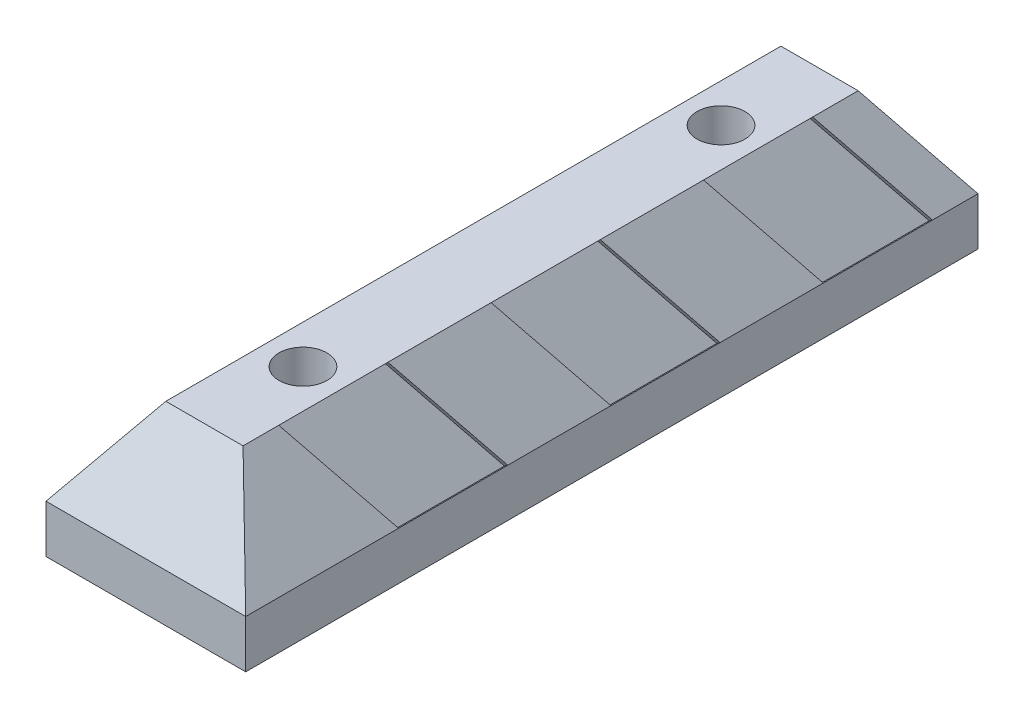
SolidWorks part; units mm, degrees
ref_plane "Alzado" through (0, 0, 0) normal (0, 0, 1) x (1, 0, 0)
ref_plane "Planta" through (0, 0, 0) normal (0, 1, 0) x (1, 0, 0)
ref_plane "Vista lateral" through (0, 0, 0) normal (1, 0, 0) x (0, 0, -1)
sketch "Croquis1" plane through (0, 0, 0) normal (0, 0, 1) x (1, 0, 0)
  line L1 (0, 0) -> (150, 0)
  line L2 (0, 0) -> (0, 102)
  line L3 (0, 102) -> (150, 102)
  line L4 (150, 0) -> (150, 102)
  dimension "D1" = 150
  dimension "D2" = 102
extrude "Saliente-Extruir1" add sketch "Croquis1" along normal blind 550
sketch "Croquis2" plane through (0, 0, 550) normal (0, 0, 1) x (1, 0, 0)
  line L0 (0, 36) -> (46, 102)
  line L1 (0, 102) -> (0, 0) construction
  line L2 (150, 102) -> (0, 102) construction
  line L3 (75, 102) -> (75, 0) construction
  line L4 (0, 0) -> (150, 0) construction
  line L5 (150, 36) -> (104, 102)
  line L6 (46, 102) -> (-6.7267, 105.185)
  line L7 (-6.7267, 105.185) -> (0, 36)
  line L8 (104, 102) -> (154.5473, 106.586)
  line L9 (154.5473, 106.586) -> (150, 36)
  dimension "D1" = 36
  dimension "D2" = 46
extrude "Cortar-Extruir1" cut sketch "Croquis2" against normal up to surface (550 mm away) up to face at (75, 51, 0)
sketch "Croquis3" plane through (0, 0, 0) normal (-1, 0, 0) x (0, 0, 1)
  line L0 (0, 36) -> (44, 102)
  line L1 (0, 102) -> (550, 102) construction
  line L2 (44, 102) -> (0, 102)
  line L3 (0, 102) -> (0, 36)
  line L4 (275, 102) -> (275, 0) construction
  line L5 (550, 0) -> (0, 0) construction
  line L6 (550, 36) -> (506, 102)
  line L7 (550, 102) -> (550, 36)
  line L8 (506, 102) -> (550, 102)
  dimension "D1" = 44
extrude "Cortar-Extruir2" cut sketch "Croquis3" against normal blind 500
sketch "Croquis4" plane through (-16.8875, 11.7701, 0) normal (-0.8204, 0.5718, 0) x (0, 0, 1)
  line L0 (34.1939, 29.5343) -> (78.1939, 109.9831)
  line L1 (0, 29.5343) -> (550, 29.5343) construction
  line L2 (44, 109.9831) -> (506, 109.9831) construction
  line L3 (78.1939, 109.9831) -> (160.1939, 109.9831)
  line L4 (160.1939, 109.9831) -> (116.1939, 29.5343)
  line L5 (116.1939, 29.5343) -> (34.1939, 29.5343)
  line L6 (44, 109.9831) -> (0, 29.5343) construction
  line L7 (193.7, 29.5343) -> (237.7, 109.9831)
  line L8 (237.7, 109.9831) -> (319.7, 109.9831)
  line L9 (319.7, 109.9831) -> (275.7, 29.5343)
  line L10 (275.7, 29.5343) -> (193.7, 29.5343)
  line L11 (353.2061, 29.5343) -> (397.2061, 109.9831)
  line L12 (397.2061, 109.9831) -> (479.2061, 109.9831)
  line L13 (479.2061, 109.9831) -> (435.2061, 29.5343)
  line L14 (435.2061, 29.5343) -> (353.2061, 29.5343)
  dimension "D1" = 30
  dimension "D2" = 82
  dimension "D3" = 82
  dimension "D4" = 68
  dimension "D5" = 82
  dimension "D6" = 68
extrude "Cortar-Extruir3" cut sketch "Croquis4" against normal blind 3
sketch "Croquis5" plane through (117.8455, 82.1347, 0) normal (0.8204, 0.5718, 0) x (0, 0, -1)
  line L0 (-78.1939, 24.2142) -> (-34.1939, -56.2346)
  line L1 (-44, 24.2142) -> (-506, 24.2142) construction
  line L2 (0, -56.2346) -> (-550, -56.2346) construction
  line L3 (-34.1939, -56.2346) -> (-116.1939, -56.2346)
  line L4 (-116.1939, -56.2346) -> (-160.1939, 24.2142)
  line L5 (-160.1939, 24.2142) -> (-78.1939, 24.2142)
  line L6 (0, -56.2346) -> (-44, 24.2142) construction
  line L7 (-193.7, -56.2346) -> (-237.7, 24.2142)
  line L8 (-237.7, 24.2142) -> (-319.7, 24.2142)
  line L9 (-319.7, 24.2142) -> (-275.7, -56.2346)
  line L10 (-275.7, -56.2346) -> (-193.7, -56.2346)
  line L11 (-397.2061, 24.2142) -> (-353.2061, -56.2346)
  line L12 (-353.2061, -56.2346) -> (-435.2061, -56.2346)
  line L13 (-435.2061, -56.2346) -> (-479.2061, 24.2142)
  line L14 (-479.2061, 24.2142) -> (-397.2061, 24.2142)
  dimension "D1" = 30
  dimension "D2" = 82
  dimension "D3" = 68
  dimension "D4" = 82
  dimension "D5" = 68
  dimension "D6" = 82
extrude "Cortar-Extruir4" cut sketch "Croquis5" against normal blind 3
sketch "Croquis6" plane through (0, 102, 0) normal (0, 1, 0) x (1, 0, 0)
  line L0 (75, -44) -> (75, -118) construction
  line L2 (75, -506) -> (75, -432) construction
  line L4 (104, -44) -> (46, -44) construction
  line L5 (150, 0) -> (0, 0) construction
  line L6 (104, -506) -> (46, -506) construction
  line L7 (150, -550) -> (0, -550) construction
  circle A0 centre (75, -118) radius 6.35
  circle A1 centre (75, -432) radius 6.35
  dimension "D2" = 12.7
  dimension "D4" = 12.7
  dimension "D3" = 118
  dimension "D1" = 118
extrude "Cortar-Extruir5" cut sketch "Croquis6" against normal up to surface (102 mm away) up to face at (75, 0, 275)
sketch "Croquis7" plane through (0, 102, 0) normal (0, 1, 0) x (1, 0, 0)
  circle A0 centre (75, -118) radius 18
  circle A1 centre (75, -432) radius 18
  dimension "D1" = 36
  dimension "D2" = 36
extrude "Cortar-Extruir6" cut sketch "Croquis7" against normal blind 41
